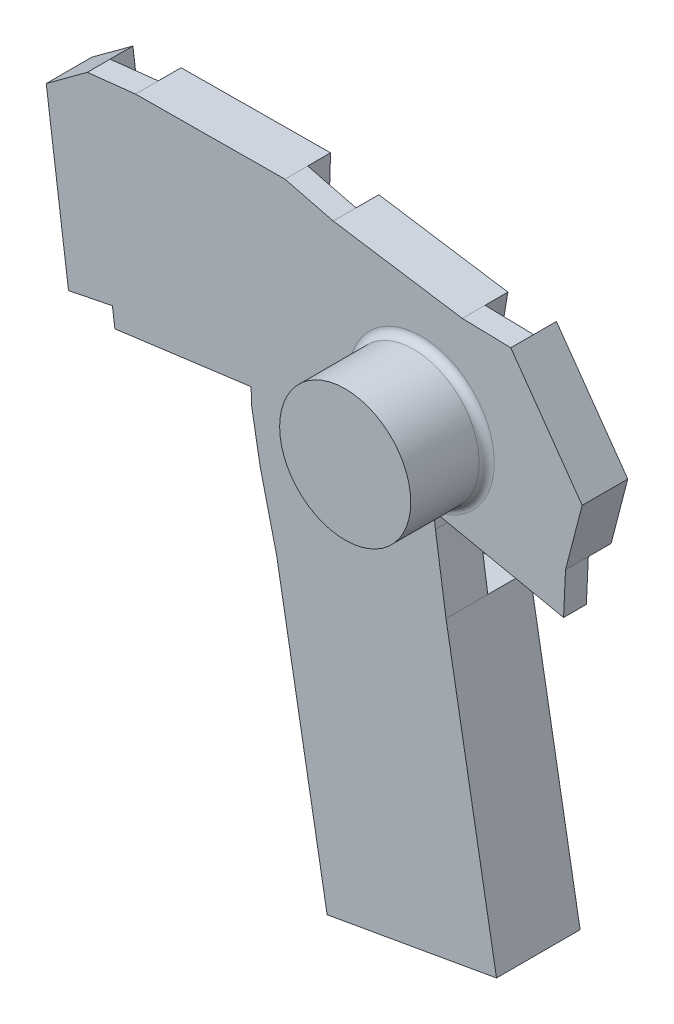
SolidWorks part; units mm, degrees
ref_plane "Front Plane" through (0, 0, 0) normal (0, 0, 1) x (1, 0, 0)
ref_plane "Top Plane" through (0, 0, 0) normal (0, 1, 0) x (1, 0, 0)
ref_plane "Right Plane" through (0, 0, 0) normal (1, 0, 0) x (0, 0, -1)
sketch "Sketch1" plane through (0, 0, 0) normal (0, 0, 1) x (1, 0, 0)
  line L0 (-149.1801, 22.2907) -> (-150.3662, 19.9974) construction
  line L1 (-149.1801, 22.2907) -> (-152.3205, 46.0207) construction
  line L2 (-146.4621, 47.3165) -> (-143.3851, 23.5515) construction
  line L3 (-143.3851, 23.5515) -> (-141.79, 22.7266) construction
  line L4 (-141.79, 22.7266) -> (-141.3802, 22.857) construction
  line L5 (-141.3802, 22.857) -> (-128.7574, 23.6178) construction
  line L6 (-128.7574, 23.6178) -> (-128.2753, 23.6333) construction
  line L7 (-128.2753, 23.6333) -> (-126.7255, 25.2858) construction
  line L8 (-126.7255, 25.2858) -> (-126.0653, 46.2312) construction
  line L9 (-120.053, 46.5511) -> (-120.734, 25.2854) construction
  line L10 (-120.734, 25.2854) -> (-119.28, 23.9218) construction
  line L11 (-119.28, 23.9218) -> (-118.7979, 23.9372) construction
  line L12 (-118.7979, 23.9372) -> (-107.3943, 22.5434) construction
  line L13 (-107.3943, 22.5434) -> (-105.6431, 23.9131) construction
  line L14 (-105.6431, 23.9131) -> (-102.5368, 42.2864) construction
  line L15 (-96.7402, 41.0906) -> (-99.7777, 22.6786) construction
  line L16 (-99.7777, 22.6786) -> (-98.565, 20.8226) construction
  line L17 (-98.565, 20.8226) -> (-84.7158, 17.9194) construction
  line L18 (-84.7158, 17.9194) -> (-80.3416, 20.7775) construction
  line L19 (-80.3416, 20.7775) -> (-79.5678, 26.975) construction
  line L20 (-81.3041, 12.0037) -> (-106.5392, 17.2938) construction
  line L21 (-106.5392, 17.2938) -> (-119.4272, 18.9056) construction
  line L22 (-119.4272, 18.9056) -> (-128.1457, 18.6259) construction
  line L23 (-128.1457, 18.6259) -> (-141.0782, 17.8465) construction
  line L24 (-141.0782, 17.8465) -> (-149.9979, 15.008) construction
  line L25 (-104.945, 5.9137) -> (-127.6247, 1.9094) construction
  line L26 (-127.6247, 1.9094) -> (-118.1521, -51.7421) construction
  line L27 (-104.945, 5.9137) -> (-98.2665, -31.912) construction
  line L28 (-98.3795, -31.9319) -> (-121.2931, -35.9775) construction
  line L29 (-98.6117, -1.1995) -> (-95.2176, 1.1496) construction
  line L30 (-95.2176, 1.1496) -> (-88.4302, -0.0854) construction
  line L31 (-88.4302, -0.0854) -> (-86.1587, -0.9485) construction
  line L32 (-86.1587, -0.9485) -> (-84.556, -3.0952) construction
  line L33 (-98.6117, -1.1995) -> (-94.0382, -27.1036) construction
  line L34 (-94.0382, -27.1036) -> (-89.7126, -30.1309) construction
  line L35 (-125.1132, 7.4302) -> (-109.7534, 10.1421) construction
  line L36 (-109.7534, 10.1421) -> (-106.2916, 15.0884) construction
  line L37 (-106.2916, 15.0884) -> (-106.5392, 17.2938) construction
  line L38 (-125.1132, 7.4302) -> (-129.7478, 10.6738) construction
  line L39 (-129.7478, 10.6738) -> (-130.8744, 17.0544) construction
  line L40 (-130.8744, 17.0544) -> (-130.9273, 18.4583) construction
  line L41 (-145.9639, 45.0264) -> (-143.2002, 23.6811)
  line L43 (-149.3917, 22.317) -> (-150.5058, 20.1629)
  line L44 (-143.2002, 23.6811) -> (-141.7717, 22.9423)
  line L45 (-126.9231, 25.3675) -> (-128.3533, 23.8425)
  line L46 (-126.9342, 25.0132) -> (-126.9326, 25.065)
  line L47 (-145.9639, 45.0264) -> (-126.2991, 45.16)
  line L48 (-119.9486, 43.5633) -> (-120.5312, 25.3694)
  line L49 (-126.9231, 25.3675) -> (-126.2991, 45.16)
  line L50 (-141.4171, 23.0551) -> (-128.3533, 23.8425)
  line L51 (-118.7889, 24.1376) -> (-107.4523, 22.7519)
  line L52 (-141.7717, 22.9423) -> (-141.4171, 23.0551)
  line L53 (-150.5058, 20.1629) -> (-151.0292, 19.9963)
  line L54 (-119.9486, 43.5633) -> (-102.9642, 40.958)
  line L55 (-150.3662, 19.9974) -> (-150.979, 19.8024) construction
  line L56 (-150.979, 19.8024) -> (-154.9203, 19.0069) construction
  line L57 (-154.9203, 19.0069) -> (-158.2301, 18.3441) construction
  line L58 (-152.3048, 44.3299) -> (-149.3917, 22.317)
  line L61 (-154.9103, 19.213) -> (-151.0292, 19.9963)
  line L62 (-154.9103, 19.213) -> (-157.7083, 40.356)
  line L63 (-157.7083, 40.356) -> (-152.3048, 44.3299)
  line L64 (-96.5844, 40.8061) -> (-99.5677, 22.7228)
  line L65 (-120.5312, 25.3694) -> (-119.2036, 24.1243)
  line L66 (-99.5677, 22.7228) -> (-98.4429, 21.0013)
  line L67 (-96.5844, 40.8061) -> (-87.1944, 27.5433)
  line L68 (-87.1944, 27.5433) -> (-89.386, 19.1027)
  line L69 (-98.4429, 21.0013) -> (-89.386, 19.1027)
  line L70 (-128.1364, 18.4261) -> (-119.4364, 18.7052)
  line L71 (-119.4364, 18.7052) -> (-106.7204, 17.1149)
  line L72 (-130.7201, 18.2704) -> (-128.1364, 18.4261)
  line L73 (-109.8698, 10.3246) -> (-106.4988, 15.1412)
  line L74 (-109.8698, 10.3246) -> (-125.0664, 7.6415)
  line L75 (-125.0664, 7.6415) -> (-129.5652, 10.7901)
  line L77 (-130.675, 17.0757) -> (-130.7201, 18.2704)
  line L78 (-127.393, 1.7472) -> (-105.1072, 5.682)
  line L79 (-106.7204, 17.1149) -> (-106.4988, 15.1412)
  line L80 (-98.4635, -31.9468) -> (-120.7493, -35.8815)
  line L81 (-120.7493, -35.8815) -> (-127.393, 1.7472)
  line L82 (-105.1072, 5.682) -> (-98.4635, -31.9468)
  line L83 (-129.5652, 10.7901) -> (-130.675, 17.0757)
  line L84 (-119.2036, 24.1243) -> (-118.7889, 24.1376)
  line L86 (-107.4523, 22.7519) -> (-105.8274, 24.0229)
  line L88 (-105.8274, 24.0229) -> (-102.9642, 40.958)
  point P50 (-127.5004, 24.4595)
  dimension "D2" = 0.2
  dimension "D5" = 0.2
  dimension "D6" = 0.2
  dimension "D7" = 0.2
  dimension "D10" = 0.2
  dimension "D14" = 0.2
  dimension "D17" = 0.2
  dimension "D21" = 0.2
  dimension "D22" = 0.2
  dimension "D24" = 0.2
  dimension "D25" = 0.2
  dimension "D26" = 0.2
  dimension "D28" = 0.2
  dimension "D29" = 0.2
  dimension "D31" = 0.2
extrude "Boss-Extrude1" add sketch "Sketch1" against normal blind 3 contours L63 L62 L61 L53 L43 L58 | L44 L52 L50 L45 L49 L47 L41 | L86 L88 L54 L48 L65 L84 L51 | L66 L69 L68 L67 L64 | L83 L75 L74 L73 L79 L71 L70 L72 L77 | L82 L78 L81 L80
sketch "Sketch2" plane through (0, 0, 0) normal (0, 0, 1) x (1, 0, 0)
  line L0 (-154.7788, 18.2193) -> (-149.0037, 19.385)
  line L1 (-154.9103, 19.213) -> (-151.0292, 19.9963) construction
  line L2 (-157.7083, 40.356) -> (-154.7788, 18.2193)
  line L3 (-157.7083, 40.356) -> (-152.3048, 44.3299)
  line L4 (-152.3048, 44.3299) -> (-145.9639, 45.0264)
  line L5 (-145.9639, 45.0264) -> (-126.2991, 45.16)
  line L6 (-126.2991, 45.16) -> (-119.9486, 43.5633)
  line L7 (-119.9486, 43.5633) -> (-102.9642, 40.958)
  line L8 (-102.9642, 40.958) -> (-96.5844, 40.8061)
  line L9 (-96.5844, 40.8061) -> (-87.1944, 27.5433)
  line L10 (-87.1944, 27.5433) -> (-89.386, 19.1027)
  line L11 (-87.1944, 27.5433) -> (-89.386, 19.1027) construction
  line L12 (-149.0037, 19.385) -> (-148.6764, 16.9119)
  line L14 (-148.6764, 16.9119) -> (-130.7583, 19.2831)
  line L15 (-130.675, 17.0757) -> (-130.7583, 19.2831)
  line L16 (-127.393, 1.7472) -> (-120.7493, -35.8815)
  line L17 (-127.393, 1.7472) -> (-129.5652, 10.7901)
  line L18 (-129.5652, 10.7901) -> (-130.675, 17.0757)
  line L19 (-120.7493, -35.8815) -> (-98.4635, -31.9468)
  line L20 (-98.4635, -31.9468) -> (-105.1072, 5.682)
  line L21 (-105.1072, 5.682) -> (-106.4988, 15.1412)
  line L22 (-109.8698, 10.3246) -> (-106.4988, 15.1412) construction
  line L23 (-106.4988, 15.1412) -> (-106.7204, 17.1149)
  line L24 (-106.7204, 17.1149) -> (-89.6401, 13.5343)
  line L25 (-89.6401, 13.5343) -> (-89.386, 19.1027)
  dimension "D1" = 1
extrude "Boss-Extrude2" add sketch "Sketch2" along normal blind 3
sketch "Sketch3" plane through (0, 0, -3) normal (0, 0, -1) x (-1, 0, 0)
  line L0 (106.7204, 17.1149) -> (106.4988, 15.1412)
  line L1 (106.4988, 15.1412) -> (109.8698, 10.3246)
  line L2 (109.8698, 10.3246) -> (106.4988, 15.1412)
  line L3 (106.7204, 17.1149) -> (119.4364, 18.7052)
  line L4 (119.4364, 18.7052) -> (130.7201, 18.2704)
  line L5 (130.7201, 18.2704) -> (130.675, 17.0757)
  line L6 (130.675, 17.0757) -> (129.5652, 10.7901)
  line L7 (109.8698, 10.3246) -> (125.0664, 7.6415)
  line L8 (125.0664, 7.6415) -> (129.5652, 10.7901)
  line M1 (129.5652, 10.7901) -> (130.675, 17.0757)
  line M2 (130.675, 17.0757) -> (130.7201, 18.2704)
  line M5 (119.4364, 18.7052) -> (106.7204, 17.1149)
  line M6 (106.7204, 17.1149) -> (106.4988, 15.1412)
  line M7 (106.4988, 15.1412) -> (109.8698, 10.3246)
  line M8 (109.8698, 10.3246) -> (125.0664, 7.6415)
  line M9 (125.0664, 7.6415) -> (129.5652, 10.7901)
extrude "Boss-Extrude3" add sketch "Sketch3" along normal blind 4 contours L4 M5 M6 M7 M8 M9 M1 M2
sketch "Sketch4" plane through (0, 0, -3) normal (0, 0, -1) x (-1, 0, 0)
  line L0 (105.1072, 5.682) -> (127.393, 1.7472)
  line L1 (127.393, 1.7472) -> (120.7493, -35.8815)
  line L2 (120.7493, -35.8815) -> (98.4635, -31.9468)
  line L3 (98.4635, -31.9468) -> (105.1072, 5.682)
extrude "Boss-Extrude4" add sketch "Sketch4" along normal blind 5
sketch "Sketch5" plane through (0, 0, 0) normal (0, 0, -1) x (-1, 0, 0)
  line L0 (106.4988, 15.1412) -> (105.1072, 5.682)
  line L1 (105.1072, 5.682) -> (127.393, 1.7472)
  line L2 (127.393, 1.7472) -> (129.5652, 10.7901)
  line L3 (129.5652, 10.7901) -> (125.0664, 7.6415)
  line L4 (125.0664, 7.6415) -> (109.8698, 10.3246)
  line L5 (109.8698, 10.3246) -> (106.4988, 15.1412)
extrude "Boss-Extrude5" add sketch "Sketch5" along normal blind 2.5
sketch "Sketch7" plane through (0, 0, 3) normal (0, 0, 1) x (1, 0, 0)
  circle A0 centre (-108.375, 26.6141) radius 8.625
  dimension "D1" = 17.25
extrude "Boss-Extrude6" add sketch "Sketch7" along normal blind 10
fillet "Fillet1" radius 1 1 edges at (-99.75, 26.6141, 3)
